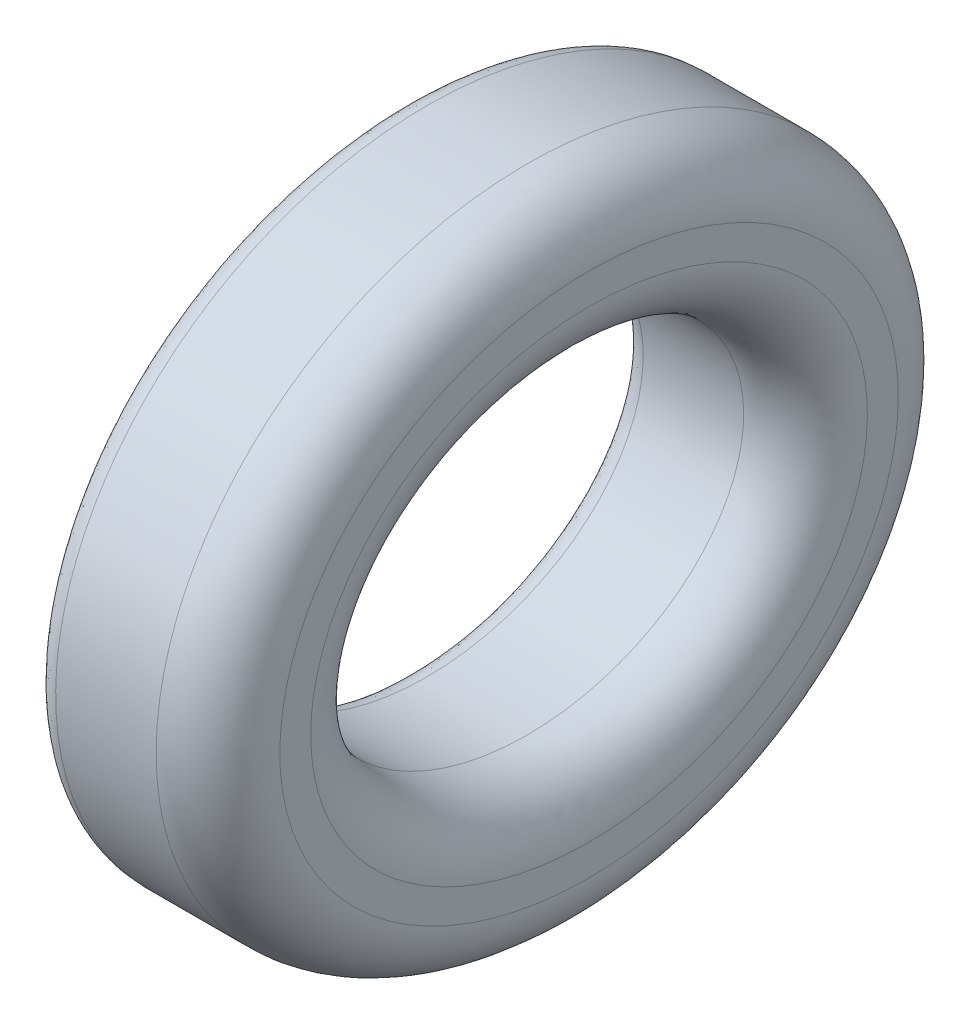
SolidWorks part; units mm, degrees
ref_plane "Front Plane" through (0, 0, 0) normal (1, 0, 0) x (0, 1, 0)
ref_plane "Top Plane" through (0, 0, 0) normal (0, 0, 1) x (0, 1, 0)
ref_plane "Right Plane" through (0, 0, 0) normal (0, 1, 0) x (-1, 0, 0)
ref_plane "Plane_x_+26p0" through (26, 0, 0) normal (1, 0, 0) x (0, 1, 0)
sketch "Sketch1" plane through (26, 0, 0) normal (1, 0, 0) x (0, 1, 0)
  ellipse E0 centre (0, -56) end of major axis (0, -104) minor radius 42
  ellipse E1 centre (0, -56) end of major axis (0, -84) minor radius 22
extrude "Pad" add sketch "Sketch1" along normal mid plane 24
fillet "FaceRound" radius 8 2 edges at (38, 0, -28) (38, 0, -8)
fillet "BaseRound" radius 3 2 edges at (14, 0, -28) (14, 0, -8)
